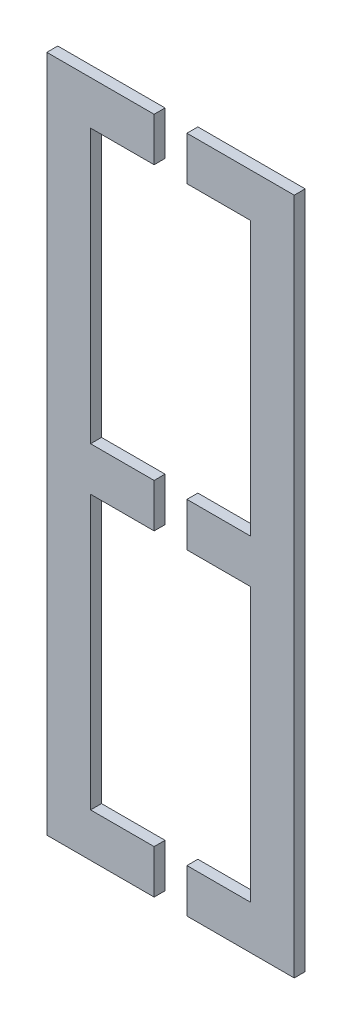
SolidWorks part; units mm, degrees
ref_plane "Alzado" through (0, 0, 0) normal (0, 0, 1) x (1, 0, 0)
ref_plane "Planta" through (0, 0, 0) normal (0, 1, 0) x (1, 0, 0)
ref_plane "Vista lateral" through (0, 0, 0) normal (1, 0, 0) x (0, 0, -1)
sketch "Croquis1" plane through (0, 0, 0) normal (0, 0, 1) x (1, 0, 0)
  line L0 (0, 0) -> (62.3, 0)
  line L1 (62.3, 0) -> (62.3, 25.4)
  line L2 (62.3, 25.4) -> (25.4, 25.4)
  line L3 (25.4, 25.4) -> (25.4, 184.125)
  line L4 (25.4, 184.125) -> (62.3, 184.125)
  line L5 (62.3, 184.125) -> (62.3, 209.525)
  line L6 (62.3, 209.525) -> (25.4, 209.525)
  line L7 (25.4, 209.525) -> (25.4, 368.25)
  line L8 (25.4, 368.25) -> (62.3, 368.25)
  line L9 (62.3, 368.25) -> (62.3, 393.65)
  line L10 (62.3, 393.65) -> (0, 393.65)
  line L11 (0, 393.65) -> (0, 0)
  line L12 (71.825, 0) -> (71.825, 360) construction
  line L13 (81.35, 184.125) -> (81.35, 209.525)
  line L14 (81.35, 209.525) -> (118.25, 209.525)
  line L15 (118.25, 184.125) -> (81.35, 184.125)
  line L16 (118.25, 25.4) -> (118.25, 184.125)
  line L17 (81.35, 25.4) -> (118.25, 25.4)
  line L18 (81.35, 0) -> (81.35, 25.4)
  line L19 (143.65, 0) -> (81.35, 0)
  line L20 (118.25, 209.525) -> (118.25, 368.25)
  line L21 (143.65, 393.65) -> (143.65, 0)
  line L22 (118.25, 368.25) -> (81.35, 368.25)
  line L23 (81.35, 368.25) -> (81.35, 393.65)
  line L24 (81.35, 393.65) -> (143.65, 393.65)
  point P28 (0, 0)
  dimension "D1" = 25.4
  dimension "D2" = 393.65
  dimension "D3" = 71.825
  dimension "D4" = 25.4
  dimension "D5" = 9.525
extrude "Saliente-Extruir1" add sketch "Croquis1" along normal blind 6.35
